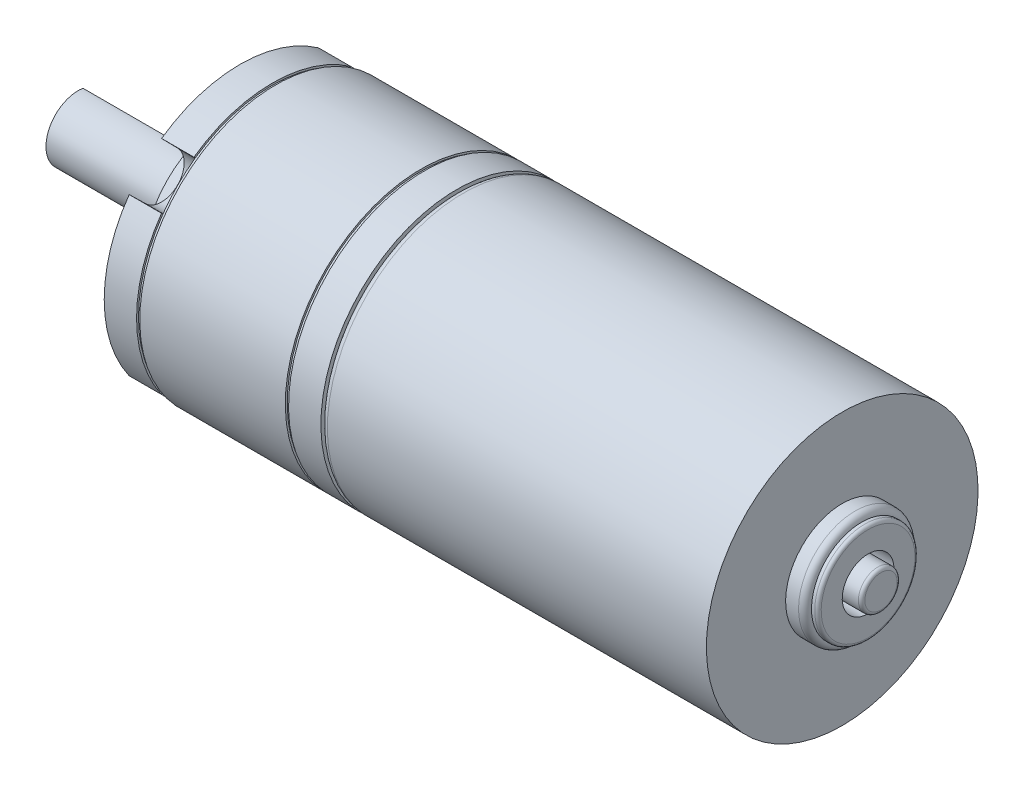
SolidWorks part; units mm, degrees
ref_plane "Front Plane" through (0, 0, 0) normal (0, 0, 1) x (1, 0, 0)
ref_plane "Top Plane" through (0, 0, 0) normal (0, 1, 0) x (1, 0, 0)
ref_plane "Right Plane" through (0, 0, 0) normal (1, 0, 0) x (0, 0, -1)
sketch "Sketch1" plane through (0, 0, 0) normal (0, 0, 1) x (1, 0, 0)
  line L0 (-106.2949, 0) -> (107.9882, 0) construction
  line L1 (0, 0) -> (59.6, 0)
  line L2 (-33.5, 0) -> (0, 0)
  line L3 (-33.5, 0) -> (-33.5, 21)
  line L4 (-33.5, 21) -> (-28.5, 21)
  line L5 (0, 0) -> (0, 20)
  line L6 (0, 0) -> (0, 21)
  line L7 (1, 21) -> (59.6, 21)
  line L8 (59.6, 0) -> (59.6, 21)
  line L9 (-33.5, 0) -> (-35.5, 0)
  line L10 (-33.5, 0) -> (-33.5, 13)
  line L11 (-33.5, 13) -> (-35.5, 13)
  line L12 (-35.5, 0) -> (-35.5, 13)
  line L13 (-35.5, 0) -> (-58.5, 0)
  line L14 (-35.5, 0) -> (-35.5, 5)
  line L15 (-35.5, 5) -> (-58.5, 5)
  line L16 (-58.5, 0) -> (-58.5, 5)
  line L17 (59.6, 0) -> (62.6, 0)
  line L18 (59.6, 0) -> (59.6, 8.75)
  line L19 (59.6, 8.75) -> (61.6, 8.75)
  line L20 (62.6, 0) -> (62.6, 7.75)
  line L21 (-28.5, 20.7) -> (-28, 20.7)
  line L22 (-28.5, 20.7) -> (-28.5, 0)
  line L23 (-28.5, 0) -> (-28, 0)
  line L24 (-28, 20.7) -> (-28, 0)
  line L25 (-5.5, 20.7) -> (-5, 20.7)
  line L26 (-5.5, 20.7) -> (-5.5, 0)
  line L27 (-5.5, 0) -> (-5, 0)
  line L28 (-5, 20.7) -> (-5, 0)
  line L29 (62.6, 0) -> (63.6, 0)
  line L30 (62.6, 0) -> (62.6, 7.75)
  line L31 (62.6, 7.75) -> (63.1, 7.75)
  line L32 (63.6, 0) -> (63.6, 7.25)
  line L33 (63.6, 0) -> (65.6, 0)
  line L34 (63.6, 0) -> (63.6, 3)
  line L35 (63.6, 3) -> (65.1, 3)
  line L36 (65.6, 0) -> (65.6, 2.5)
  line L37 (-5.5, 20.7) -> (-5.5, 21)
  line L38 (-5, 20.7) -> (-5, 21)
  line L39 (-5, 21) -> (0, 21)
  line L40 (-28.5, 20.7) -> (-28.5, 21)
  line L41 (-28, 20.7) -> (-28, 21)
  line L42 (-28, 21) -> (-5.5, 21)
  arc A0 (0, 20) -> (1, 21) centre (1, 20) cw
  arc A1 (62.6, 7.75) -> (61.6, 8.75) centre (61.6, 7.75) ccw
  arc A2 (63.6, 7.25) -> (63.1, 7.75) centre (63.1, 7.25) ccw
  arc A3 (65.6, 2.5) -> (65.1, 3) centre (65.1, 2.5) ccw
  point P30 (62.6, 8.75)
  point P34 (63.6, 7.75)
  point P40 (65.6, 3)
  dimension "D18" = 1
  dimension "D19" = 1
  dimension "D21" = 0.5
  dimension "D24" = 0.5
  dimension "D1" = 33.5
  dimension "D2" = 59.6
  dimension "D3" = 21
  dimension "D4" = 2
  dimension "D5" = 13
  dimension "D6" = 23
  dimension "D7" = 5
  dimension "D8" = 3
  dimension "D9" = 8.75
  dimension "D10" = 0.5
  dimension "D11" = 0.3
  dimension "D13" = 0.5
  dimension "D14" = 0.3
  dimension "D16" = 5
  dimension "D17" = 5
  dimension "D20" = 1
  dimension "D22" = 3
  dimension "D23" = 2
revolve "Revolve3" add sketch "Sketch1" angle 360 about L0
sketch "Sketch2" plane through (-33.5, 0, 0) normal (-1, 0, 0) x (0, 0, 1)
  line L0 (0, -24.5732) -> (0, 22.5981) construction
  circle A0 centre (0, 17.5) radius 2.1
  circle A1 centre (17.5, 0) radius 2.1
  circle A2 centre (0, -17.5) radius 2.1
  circle A3 centre (-17.5, 0) radius 2.1
  point P14 (0, 0)
  dimension "D2" = 4.2
  dimension "D1" = 17.5
  dimension "D3" = 4
extrude "Cut-Extrude1" cut sketch "Sketch2" against normal blind 10
sketch "Sketch5" plane through (-58.5, 0, 0) normal (-1, 0, 0) x (0, 0, 1)
  line L0 (0, 0) -> (-18.5435, 18.5435) construction
  line L5 (0, 22.7635) -> (0, -11.4657) construction
  line L6 (-17.9624, -17.9624) -> (0, 0) construction
  line L7 (-4.9497, 0.7071) -> (-0.7071, 4.9497)
  line L8 (-5.6569, 1.4142) -> (-1.4142, 5.6569)
  line L9 (-1.4142, 5.6569) -> (-0.7071, 4.9497)
  line L10 (-4.9497, 0.7071) -> (-5.6569, 1.4142)
  circle A0 centre (0, 0) radius 5 construction
  circle A3 centre (0, 0) radius 5 construction
  point P0 (-0.7658, 4.941)
  dimension "D1" = 1
  dimension "D2" = 45
extrude "Cut-Extrude2" cut sketch "Sketch5" against normal blind 16
sketch "Sketch12" plane through (-33.5, 0, 0) normal (-1, 0, 0) x (0, 0, 1)
  line L0 (0, 0) -> (0, 21.5918) construction
  line L1 (0, 0) -> (17.6504, 17.6504) construction
  line L2 (9.6297, 14.5791) -> (12.1328, 17.1404)
  line L3 (14.5791, 9.6297) -> (17.1404, 12.1328)
  line L4 (14.5791, -9.6297) -> (17.1404, -12.1328)
  line L5 (9.6297, -14.5791) -> (12.1328, -17.1404)
  line L6 (-9.6297, -14.5791) -> (-12.1328, -17.1404)
  line L7 (-14.5791, -9.6297) -> (-17.1404, -12.1328)
  line L8 (-14.5791, 9.6297) -> (-17.1404, 12.1328)
  line L9 (-9.6297, 14.5791) -> (-12.1328, 17.1404)
  arc A0 (9.6297, 14.5791) -> (14.5791, 9.6297) centre (12.1328, 12.1328) ccw
  circle A1 centre (0, 0) radius 21 construction
  arc A3 (17.1404, 12.1328) -> (12.1328, 17.1404) centre (0, 0) ccw
  arc A4 (12.1328, -17.1404) -> (17.1404, -12.1328) centre (0, 0) ccw
  arc A5 (14.5791, -9.6297) -> (9.6297, -14.5791) centre (12.1328, -12.1328) ccw
  arc A6 (-17.1404, -12.1328) -> (-12.1328, -17.1404) centre (0, 0) ccw
  arc A7 (-9.6297, -14.5791) -> (-14.5791, -9.6297) centre (-12.1328, -12.1328) ccw
  arc A8 (-12.1328, 17.1404) -> (-17.1404, 12.1328) centre (0, 0) ccw
  arc A9 (-14.5791, 9.6297) -> (-9.6297, 14.5791) centre (-12.1328, 12.1328) ccw
  point P30 (0, 0)
  dimension "D2" = 7
  dimension "D3" = 4
  dimension "D1" = 45
extrude "Cut-Extrude3" cut sketch "Sketch12" against normal blind 5
sketch "Sketch14" plane through (-28.5, 0, 0) normal (-1, 0, 0) x (0, 0, 1)
  circle A0 centre (12.1328, 12.1328) radius 2.25
  circle A1 centre (12.1328, -12.1328) radius 2.25
  circle A2 centre (-12.1328, -12.1328) radius 2.25
  circle A3 centre (-12.1328, 12.1328) radius 2.25
  point P12 (0, 0)
  dimension "D1" = 4.5
  dimension "D2" = 4
extrude "Cut-Extrude4" cut sketch "Sketch14" against normal blind 10
sketch "Esquisse4" plane through (63.6, 0, 0) normal (1, 0, 0) x (0, 0, -1)
  circle A0 centre (0, 0) radius 3
  circle A1 centre (0, 0) radius 4
  dimension "D1" = 6
  dimension "D2" = 8
extrude "Enlèv. mat.-Extru.1" cut sketch "Esquisse4" against normal blind 4
